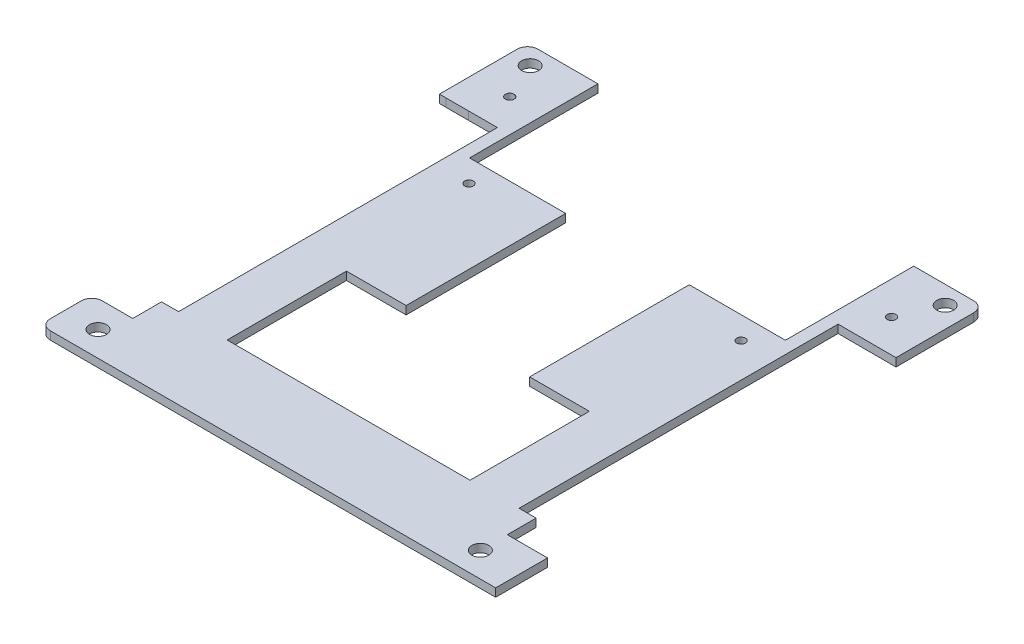
SolidWorks part; units mm, degrees
material "Copper"
ref_plane "Front Plane" through (0, 0, 0) normal (0, 0, 1) x (1, 0, 0)
ref_plane "Top Plane" through (0, 0, 0) normal (0, 1, 0) x (1, 0, 0)
ref_plane "Right Plane" through (0, 0, 0) normal (1, 0, 0) x (0, 0, -1)
sketch "Sketch1" plane through (0, 0, 0) normal (0, 1, 0) x (1, 0, 0)
  line L0 (-38.395, 30) -> (-42.73, 30)
  line L1 (-44, 31.27) -> (-44, 45)
  line L2 (42, 47) -> (30.435, 47)
  line L3 (44, 45) -> (44, 32)
  line L4 (44, 32) -> (44, 30.014)
  line L5 (44, 30.014) -> (32.824, 30.032)
  line L6 (32.824, 30.032) -> (32.824, -31.454)
  line L8 (-42, -47) -> (43.8497, -47)
  line L9 (-44, -45) -> (-44, -38.977)
  line L10 (-42, -37) -> (-38.395, -37)
  line L11 (-38.395, -37) -> (-36.1, -37)
  line L13 (23.409, -31.5) -> (-23.409, -31.5)
  line L14 (-11.909, -8.5) -> (-23.409, -8.5)
  line L15 (11.909, -8.5) -> (23.409, -8.5)
  line L16 (-11.909, -8.5) -> (-11.909, 22.2554)
  line L18 (30.435, 22.2554) -> (11.909, 22.2554)
  line L19 (-23.409, -31.5) -> (-23.409, -8.5)
  line L20 (-36.1, -37) -> (-36.1, -31.454)
  line L21 (-36.1, -31.454) -> (-32.824, -31.454)
  line L22 (-32.824, -31.454) -> (-32.824, 30.014)
  line L23 (-32.824, 30.014) -> (-38.395, 30)
  line L24 (-42.73, 30) -> (-44, 30.014)
  line L25 (-44, 30.014) -> (-44, 31.27)
  line L26 (11.909, -8.5) -> (11.909, 22.2554)
  line L28 (43.8497, -47) -> (43.8497, -37)
  line L29 (36.1, -37) -> (43.8497, -37)
  line L33 (32.824, -31.454) -> (36.1, -31.454)
  line L34 (-23.409, 13.2954) -> (-23.409, -31.5) construction
  line L35 (23.409, -31.5) -> (23.409, -8.5)
  line L36 (36.1, -31.454) -> (36.1, -37)
  line L40 (30.435, 22.2554) -> (30.435, 47)
  line L41 (-42, 47) -> (-30.435, 47)
  line L42 (-30.435, 47) -> (-30.435, 22.2554)
  line L43 (-30.435, 22.2554) -> (-11.909, 22.2554)
  circle A0 centre (40, 43.5) radius 1.6383
  circle A1 centre (-40, 43.5) radius 1.6383
  circle A2 centre (-37.6, -42.2) radius 1.6383
  circle A3 centre (36.1, -42.2) radius 1.6383
  circle A4 centre (-36.785, 36.35) radius 0.8382
  arc A5 (-42, 47) -> (-44, 45) centre (-42, 45) ccw
  arc A6 (44, 45) -> (42, 47) centre (42, 45) ccw
  circle A7 centre (-26.22, 17.9319) radius 0.8382
  circle A8 centre (26.22, 17.9319) radius 0.8382
  arc A11 (-44, -45) -> (-42, -47) centre (-42, -45) ccw
  arc A12 (-42, -37) -> (-44, -38.977) centre (-42.0115, -38.9885) ccw
  circle A13 centre (36.785, 36.368) radius 0.8382
  dimension "D2" = 73.7
  dimension "D3" = 85.7
  dimension "D4" = 80
  dimension "D5" = 85.7
extrude "Boss-Extrude1" add sketch "Sketch1" along normal blind 1.575
